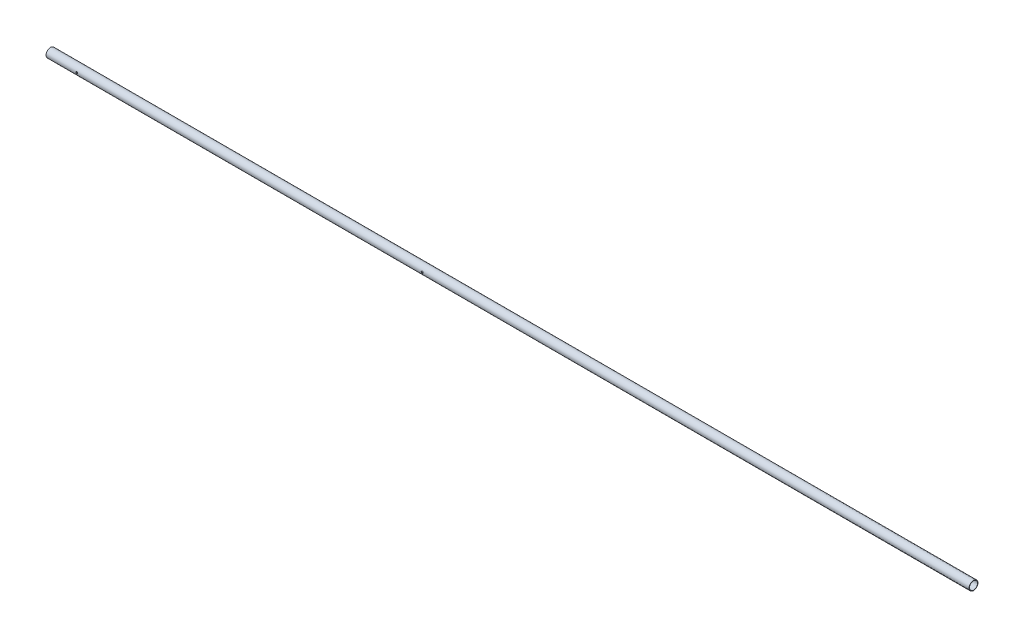
SolidWorks part; units mm, degrees
material "Galvanized Steel"
ref_plane "Front Plane" through (0, 0, 0) normal (0, 0, 1) x (1, 0, 0)
ref_plane "Top Plane" through (0, 0, 0) normal (0, 1, 0) x (1, 0, 0)
ref_plane "Right Plane" through (0, 0, 0) normal (1, 0, 0) x (0, 0, -1)
sketch "Sketch3" plane through (0, 0, 0) normal (1, 0, 0) x (0, 0, -1)
  circle A0 centre (0, 0) radius 13.3223
  circle A1 centre (0, 0) radius 14.7701
  dimension "D1" = 26.6446
  dimension "D2" = 29.5402
extrude "Boss-Extrude1" add sketch "Sketch3" along normal blind 3048
sketch "Sketch6" plane through (0, 0, 0) normal (0, 0, 1) x (1, 0, 0)
  line L0 (0, 14.7701) -> (0, -14.7701) construction
  circle A0 centre (101.6, 0) radius 3.175
  circle A1 centre (1242.06, 0) radius 3.175
  dimension "D1" = 101.6
  dimension "D2" = 1242.06
extrude "Cut-Extrude1" cut sketch "Sketch6" against normal through all and the other way through all
